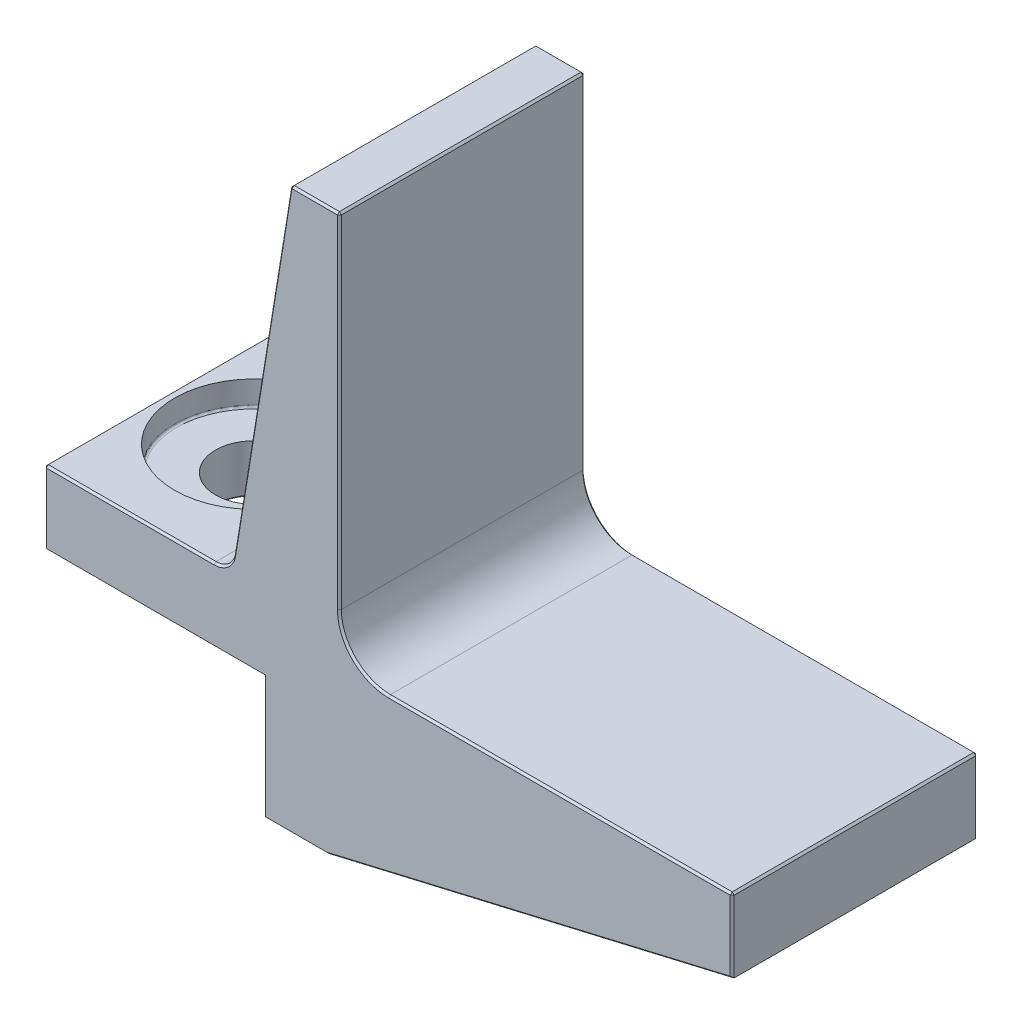
SolidWorks part; units mm, degrees
material "7075-T6 (SN)"
ref_plane "Front Plane" through (0, 0, 0) normal (0, 0, 1) x (1, 0, 0)
ref_plane "Top Plane" through (0, 0, 0) normal (0, 1, 0) x (1, 0, 0)
ref_plane "Right Plane" through (0, 0, 0) normal (1, 0, 0) x (0, 0, -1)
sketch "Sketch1" plane through (0, 0, 0) normal (0, 0, 1) x (1, 0, 0)
  line L0 (0, 0) -> (50.8, 0)
  line L1 (50.8, 0) -> (50.8, -9.525)
  line L2 (-9.8398, -5.8961) -> (-38.1608, -5.8961)
  line L3 (-38.1608, -5.8961) -> (-38.1608, 3.6289)
  line L4 (-38.1608, 3.6289) -> (-14.0308, 3.6289)
  line L5 (-14.0308, 3.6289) -> (-6.35, 50.8)
  line L6 (-6.35, 50.8) -> (0, 50.8)
  line L7 (0, 50.8) -> (0, 0)
  line L8 (-9.8398, -5.8961) -> (-9.8398, -21.7711)
  line L9 (-9.8398, -21.7711) -> (-1.5848, -21.7711)
  line L10 (-1.5848, -21.7711) -> (50.8, -9.525)
  dimension "D1" = 50.8
  dimension "D2" = 50.8
  dimension "D3" = 9.525
  dimension "D4" = 38.1608
  dimension "D5" = 6.35
  dimension "D6" = 24.13
  dimension "D7" = 28.321
  dimension "D8" = 9.525
  dimension "D9" = 15.875
  dimension "D10" = 8.255
  dimension "D11" = 3.6289
extrude "Boss-Extrude1" add sketch "Sketch1" along normal blind 31.75
hole_wizard "CBORE for 3/8 Binding Head Machine Screw1" positions "Sketch6" profile "Sketch3" counterbore size "3/8" standard "ANSI Inch" end condition through all
sketch "Sketch6" plane through (0, 3.6289, 0) normal (0, 1, 0) x (1, 0, 0)
  line L1 (-38.1608, -31.75) -> (-38.1608, 0) construction
  point P0 (-26.8578, -15.875)
  point P8 (-38.1608, -15.875)
  dimension "D1" = 11.303
sketch "Sketch3" plane through (-26.8578, 3.6289, 15.875) normal (1, 0, 0) x (0, 0, 1)
  line L0 (0, 0) -> (0, 25.4)
  line L1 (0, 25.4) -> (5.0419, 25.4)
  line L3 (5.0419, 25.4) -> (5.0419, 3.175)
  line L4 (10.3378, 3.175) -> (5.0419, 3.175)
  line L5 (10.3378, 3.175) -> (10.3378, 0)
  line L7 (10.3378, 0) -> (0, 0)
  line L11 (0, 0) -> (0, 107.95) construction
  dimension "Thru Hole Dia." = 10.0838
  dimension "Thru Hole Depth" = 25.4
  dimension "C'Bore Depth" = 3.175
fillet "Fillet1" radius 2.54 1 edges at (-14.0308, 3.6289, 15.875)
fillet "Fillet2" radius 6.35 1 edges at (0, 0, 15.875)
chamfer "Chamfer1" distance 0.254 angle 45 31 edges at (-6.35, 50.8, 15.875) (-3.175, 50.8, 0) (-10.0168, 28.2803, 0) (-14.5453, 4.2339, 0) (-27.1757, 3.6289, 0) (-38.1608, -1.1336, 0) (-24.0003, -5.8961, 0) (50.8, -4.7625, 0) (28.575, 0, 0) (1.8599, 1.8599, 0) (0, 28.575, 0) (50.8, -4.7625, 31.75) (-24.0003, -5.8961, 31.75) (-38.1608, -5.8961, 15.875) (-38.1608, -1.1336, 31.75) (-38.1608, 3.6289, 15.875) (-27.1757, 3.6289, 31.75) (-14.5453, 4.2339, 31.75) (-10.0168, 28.2803, 31.75) (-3.175, 50.8, 31.75) (0, 50.8, 15.875) (0, 28.575, 31.75) (1.8599, 1.8599, 31.75) (28.575, 0, 31.75) (50.8, 0, 15.875) (-9.8398, -13.8336, 0) (-5.7123, -21.7711, 0) (24.6076, -15.6481, 0) (24.6076, -15.6481, 31.75) (-5.7123, -21.7711, 31.75) (-9.8398, -13.8336, 31.75)
fillet "Fillet3" radius 0.254 1 edges at (-26.8578, 0.4539, 26.2128)
chamfer "Chamfer2" distance 0.254 angle 45 1 edges at (-31.8997, -5.8961, 15.875)
